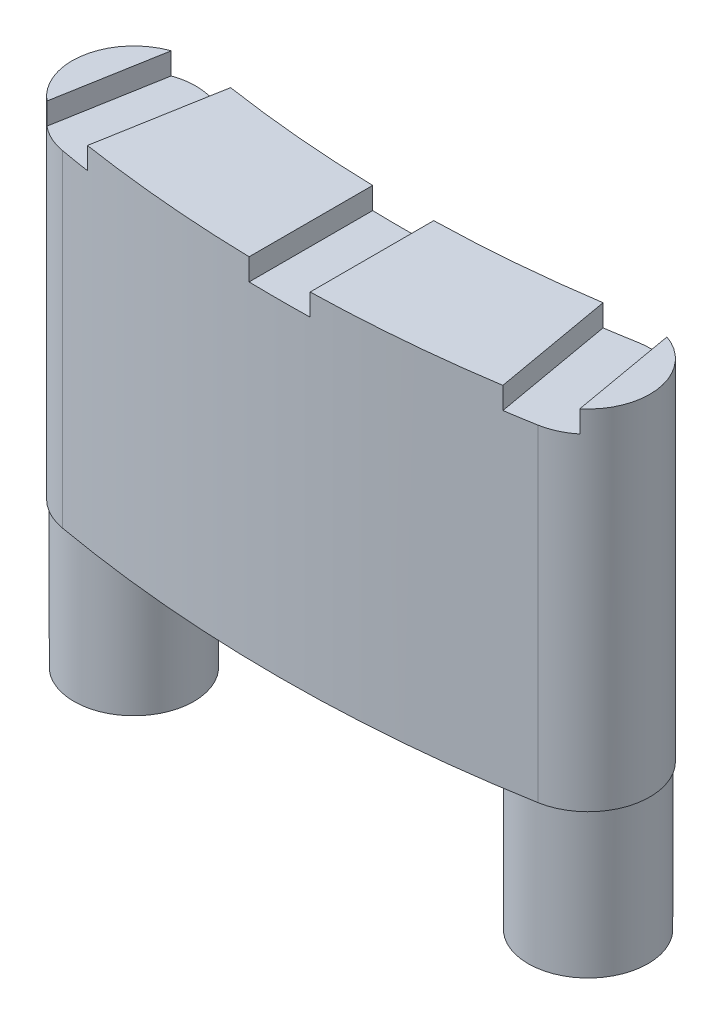
SolidWorks part; units mm, degrees
ref_plane "Front Plane" through (0, 0, 0) normal (0, 0, 1) x (1, 0, 0)
ref_plane "Top Plane" through (0, 0, 0) normal (0, 1, 0) x (1, 0, 0)
ref_plane "Right Plane" through (0, 0, 0) normal (1, 0, 0) x (0, 0, -1)
sketch "Sketch1" plane through (0, 0, 0) normal (0, 1, 0) x (1, 0, 0)
  line L0 (-16.3611, -0.9976) -> (-14.8851, 7.3733) construction
  line L1 (16.3613, -0.9994) -> (14.8852, 7.3715) construction
  line L2 (0, 22.2062) -> (0, -18.3672) construction
  arc A0 (-16.3611, -0.9976) -> (16.3613, -0.9994) centre (0.0052, 91.8206) ccw
  arc A1 (-14.8851, 7.3733) -> (14.8852, 7.3715) centre (0.0052, 91.8206) ccw
  arc A2 (-14.8851, 7.3733) -> (-16.3611, -0.9976) centre (-15.6231, 3.1879) ccw
  arc A3 (14.8852, 7.3715) -> (16.3613, -0.9994) centre (15.6336, 3.1879) cw
  circle A4 centre (0.0052, 91.8206) radius 90 construction
  point P9 (0, 6.0706)
  point P10 (0, -2.4294)
  point P13 (0, 0)
  dimension "D1" = 85.75
  dimension "D2" = 94.25
  dimension "D3" = 4.25
  dimension "D4" = 10
  dimension "D5" = 10
  dimension "D7" = 8.5
extrude "Boss-Extrude1" add sketch "Sketch1" along normal blind 24
sketch "Sketch2" plane through (0, 0, 0) normal (0, -1, 0) x (1, 0, 0)
  circle A0 centre (-15.6231, -3.1879) radius 4.25 construction
  circle A1 centre (-15.6231, -3.1879) radius 4.125
  circle A2 centre (15.6336, -3.1879) radius 4.25 construction
  circle A3 centre (15.6336, -3.1879) radius 4.125
  dimension "D1" = 8.25
  dimension "D2" = 8.5
  dimension "D3" = 8.25
extrude "Boss-Extrude2" add sketch "Sketch2" along normal blind 10
sketch "Sketch4" plane through (0, 0, 0) normal (0, -1, 0) x (1, 0, 0)
  line L0 (-14.8851, -7.3733) -> (-16.3611, 0.9976) construction
  line L1 (14.8852, -7.3715) -> (16.3613, 0.9994) construction
  line L2 (0, 11.8094) -> (0, -9.6405) construction
  line L3 (-2.1, 2.4059) -> (-2.1, -6.1406)
  line L4 (2.1, 2.4061) -> (2.1, -6.0962)
  line L5 (2.1, 11.8094) -> (2.1, -9.6405) construction
  line L6 (-2.1, 11.8094) -> (-2.1, -9.6405) construction
  arc A1 (-2.1, 2.4059) -> (2.1, 2.4061) centre (0.0002, -0.8753) cw
  arc A2 (16.3613, 0.9994) -> (-16.3611, 0.9976) centre (0.0052, -91.8206) ccw construction
  arc A3 (-2.1, -6.1406) -> (2.1, -6.0962) centre (0.6343, -66.0783) cw
  arc A4 (14.8852, -7.3715) -> (-14.8851, -7.3733) centre (0.0052, -91.8206) ccw construction
  dimension "D1" = 10
  dimension "D2" = 10
  dimension "D3" = 2.1
  dimension "D4" = 2.1
extrude "Cut-Extrude1" cut sketch "Sketch4" along normal blind 1.5 from surface at -24 starting at face at (0.0026, 24, -2.8732)
pattern_circular "CirPattern1" count 2 every 10 about axis through (0.0052, 24, -91.8206) along (0, 1, 0) of "Cut-Extrude1"
